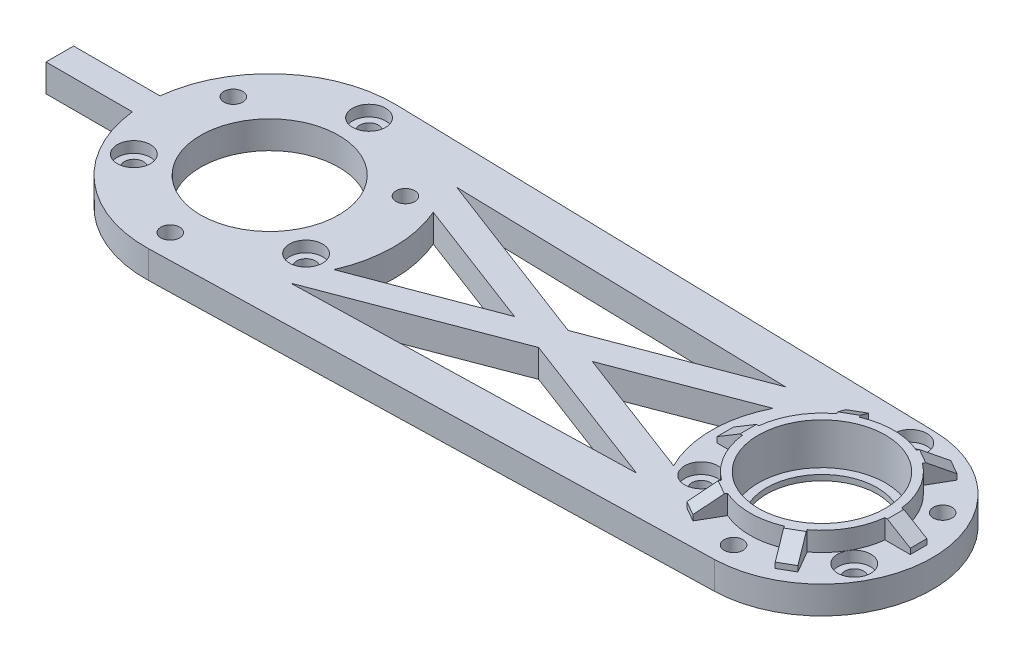
SolidWorks part; units mm, degrees
material "PLA"
ref_plane "Front Plane" through (0, 0, 0) normal (0, 0, 1) x (1, 0, 0)
ref_plane "Top Plane" through (0, 0, 0) normal (0, 1, 0) x (1, 0, 0)
ref_plane "Right Plane" through (0, 0, 0) normal (1, 0, 0) x (0, 0, -1)
sketch "Sketch1" plane through (0, 0, 0) normal (0, 1, 0) x (1, 0, 0)
  line L0 (0.5625, 22.493) -> (100.5, 19.9937)
  line L1 (0.5625, -22.493) -> (100.5, -19.9937)
  line L2 (16.6919, 15.0874) -> (85.1311, 13.3759)
  line L3 (16.6919, -15.0874) -> (85.1311, -13.3759)
  line L4 (20.6216, 9) -> (79.9214, -13.5062)
  line L5 (18.8131, 15.0344) -> (82.1394, -9)
  line L6 (20.6216, -9) -> (79.9214, 13.5062)
  line L7 (18.8131, -15.0344) -> (82.1394, 9)
  circle A0 centre (0, 0) radius 22.5
  circle A1 centre (0, 18) radius 1.7
  circle A2 centre (15.5885, 9) radius 1.7
  circle A3 centre (15.5885, -9) radius 1.7
  circle A4 centre (0, -18) radius 1.7
  circle A5 centre (-15.5885, -9) radius 1.7
  circle A6 centre (-15.5885, 9) radius 1.7
  circle A7 centre (0, 0) radius 12.5
  circle A8 centre (100, 0) radius 11.5
  circle A9 centre (100, 0) radius 20
  circle A10 centre (100, 16) radius 1.7
  circle A11 centre (113.8564, 8) radius 1.7
  circle A12 centre (113.8564, -8) radius 1.7
  circle A13 centre (100, -16) radius 1.7
  circle A14 centre (86.1436, -8) radius 1.7
  circle A15 centre (86.1436, 8) radius 1.7
  point P18 (0, 0)
  point P35 (100, 0)
  dimension "D1" = 3.4
  dimension "D3" = 45
  dimension "D5" = 25
  dimension "D6" = 23
  dimension "D10" = 40
  dimension "D11" = 3.4
  dimension "D12" = 16
  dimension "D2" = 18
  dimension "D7" = 100
  dimension "D8" = 60
  dimension "D9" = 18
  dimension "D14" = 16
  dimension "D15" = 60
  dimension "D16" = 7
  dimension "D17" = 7
  dimension "D18" = 5
  dimension "D19" = 5
  dimension "D4" = 6
  dimension "D13" = 6
extrude "Boss-Extrude1" add sketch "Sketch1" along normal blind 5 contours A0 A7 A6 A5 A4 A3 A2 A1 | A9 L0 A0 L2 | A0 L4 L6 L5 L2 | L4 L7 L5 L6 | A9 L2 L6 L5 L7 | A9 L5 L7 L4 L3 | A0 L3 L7 L4 L6 | A9 L3 A0 L1 | A9 A15 A14 A13 A12 A11 A10 A8
sketch "Sketch2" plane through (0, 5, 0) normal (0, 1, 0) x (1, 0, 0)
  circle A0 centre (0, 18) radius 3
  circle A1 centre (-15.5885, -9) radius 3
  circle A2 centre (15.5885, -9) radius 3
  circle A3 centre (100, 16) radius 3
  circle A4 centre (86.1436, -8) radius 3
  circle A5 centre (113.8564, -8) radius 3
  dimension "D1" = 6
  dimension "D2" = 6
  dimension "D3" = 6
  dimension "D4" = 6
  dimension "D5" = 6
  dimension "D6" = 6
extrude "Cut-Extrude1" cut sketch "Sketch2" against normal blind 2
sketch "Sketch3" plane through (0, 5, 0) normal (0, 1, 0) x (1, 0, 0)
  circle A0 centre (100, 0) radius 11.5
  circle A1 centre (100, 0) radius 13
  circle A2 centre (113.8564, -8) radius 3 construction
extrude "Boss-Extrude2" add sketch "Sketch3" along normal blind 3.5
sketch "Sketch4" plane through (0, 0, 0) normal (0, -1, 0) x (1, 0, 0)
  circle A0 centre (100, 0) radius 10
  circle A1 centre (100, 0) radius 11.5
  circle A2 centre (100, 0) radius 11.5 construction
  dimension "D1" = 20
extrude "Boss-Extrude3" add sketch "Sketch4" against normal blind 1
sketch "Sketch6" plane through (0, 5, 0) normal (0, 1, 0) x (1, 0, 0)
  line L1 (82.5, 1.5) -> (88.5, 1.5)
  line L2 (82.5, 1.5) -> (82.5, -1.5)
  line L3 (82.5, -1.5) -> (88.5, -1.5)
  line L4 (88.5, 1.5) -> (88.5, -1.5)
  circle A0 centre (100, 0) radius 5.408
  circle A1 centre (100, 0) radius 11.5 construction
  point P7 (82.5, 0)
  arc M10 (88.7417, -6.5) -> (100, 13) centre (100, 0) cw
  dimension "D1" = 3
  dimension "D2" = 6
extrude "Boss-Extrude4" add sketch "Sketch6" along normal up to surface (3.5 mm away) contours L2 L3 L1 M10 up to face at (100, 8.5, 13)
chamfer "Chamfer1" distance 2.5 angle 59 1 edges at (82.5, 8.5, 0)
pattern_circular "CirPattern1" count 6 over 360 about axis through (100, 0, 0) along (0, 1, 0) of "Boss-Extrude4", "Chamfer1"
sketch "Sketch7" plane through (0, 0, 0) normal (0, -1, 0) x (1, 0, 0)
  line L1 (-38, 2.5) -> (-22, 2.5)
  line L2 (-38, 2.5) -> (-38, -2.5)
  line L3 (-38, -2.5) -> (-22, -2.5)
  line L4 (-22, 2.5) -> (-22, -2.5)
  point P4 (-38, 0)
  point P5 (0, 0)
  point P7 (0, 0)
  dimension "1.6" = 16
  dimension "D2" = 5
  dimension "D3" = 22
extrude "Boss-Extrude5" add sketch "Sketch7" against normal up to surface (5 mm away) up to face at (100, 5, 0.3)
